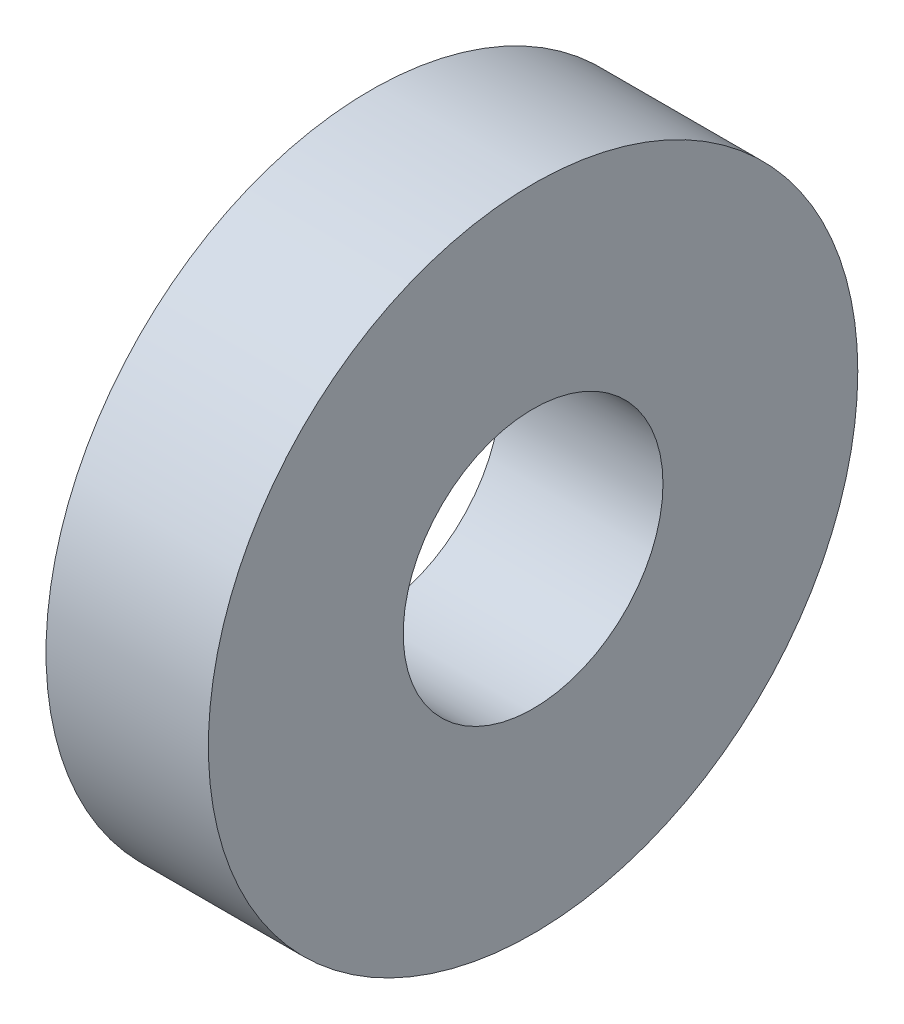
SolidWorks part; units mm, degrees
ref_plane "Спереди" through (0, 0, 0) normal (0, 0, 1) x (1, 0, 0)
ref_plane "Сверху" through (0, 0, 0) normal (0, 1, 0) x (1, 0, 0)
ref_plane "Справа" through (0, 0, 0) normal (1, 0, 0) x (0, 0, -1)
sketch "Эскиз1" plane through (0, 0, 0) normal (1, 0, 0) x (0, 0, -1)
  circle A0 centre (0, 0) radius 4
  circle A1 centre (0, 0) radius 10
extrude "Вытянуть1" add sketch "Эскиз1" along normal blind 5
